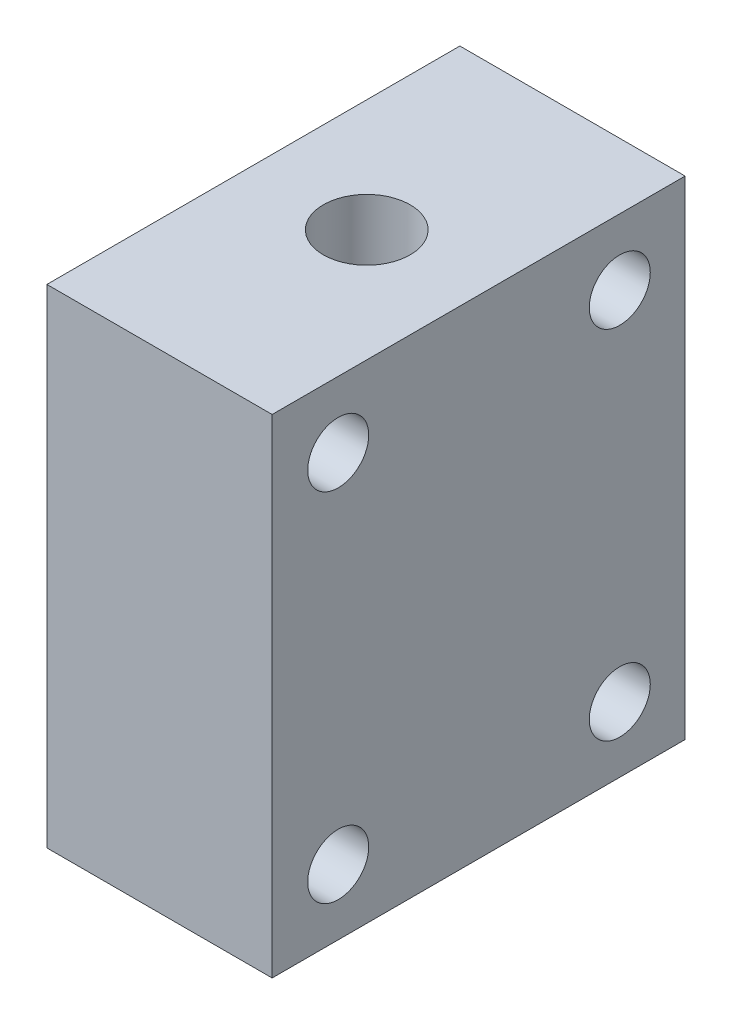
SolidWorks part; units mm, degrees
ref_plane "Front Plane" through (0, 0, 0) normal (1, 0, 0) x (0, 1, 0)
ref_plane "Top Plane" through (0, 0, 0) normal (0, 0, 1) x (0, 1, 0)
ref_plane "Right Plane" through (0, 0, 0) normal (0, 1, 0) x (-1, 0, 0)
sketch "Sketch1" plane through (0, 0, 0) normal (1, 0, 0) x (0, 1, 0)
  line L1 (0, 0) -> (82.55, 0)
  line L2 (0, 0) -> (0, 69.85)
  line L3 (0, 69.85) -> (82.55, 69.85)
  line L4 (82.55, 0) -> (82.55, 69.85)
extrude "Boss-Extrude1" add sketch "Sketch1" along normal blind 38.1
sketch "Sketch2" plane through (0, 0, 0) normal (1, 0, 0) x (0, 1, 0)
  circle A0 centre (11.049, 11.049) radius 5.1594
extrude "Cut-Extrude2" cut sketch "Sketch2" along normal through all
sketch "Sketch3" plane through (0, 0, 0) normal (1, 0, 0) x (0, 1, 0)
  circle A0 centre (71.374, 11.049) radius 5.1594
  circle A1 centre (11.049, 58.674) radius 5.1594
  circle A2 centre (71.374, 58.674) radius 5.1594
extrude "Cut-Extrude4" cut sketch "Sketch3" along normal through all
sketch "Sketch4" plane through (0, 0, 0) normal (1, 0, 0) x (0, 1, 0)
  circle A0 centre (23.622, 34.798) radius 7.3422
extrude "Cut-Extrude6" cut sketch "Sketch4" along normal blind 28.448
sketch "Sketch5" plane through (0, 0, 0) normal (1, 0, 0) x (0, 1, 0)
  circle A0 centre (23.622, 34.798) radius 12.7254
extrude "Cut-Extrude8" cut sketch "Sketch5" along normal blind 2.8194
sketch "Sketch6" plane through (0, 0, 0) normal (1, 0, 0) x (0, 1, 0)
  circle A0 centre (58.674, 34.798) radius 7.3422
extrude "Cut-Extrude10" cut sketch "Sketch6" along normal blind 28.448
sketch "Sketch7" plane through (0, 0, 0) normal (1, 0, 0) x (0, 1, 0)
  circle A0 centre (58.674, 34.798) radius 12.7254
extrude "Cut-Extrude12" cut sketch "Sketch7" along normal blind 2.8194
sketch "Sketch8" plane through (0, 0, 0) normal (0, 1, 0) x (-1, 0, 0)
  circle A0 centre (-19.05, 34.798) radius 7.3422
extrude "Cut-Extrude14" cut sketch "Sketch8" against normal blind 60.452 from offset 82.55
